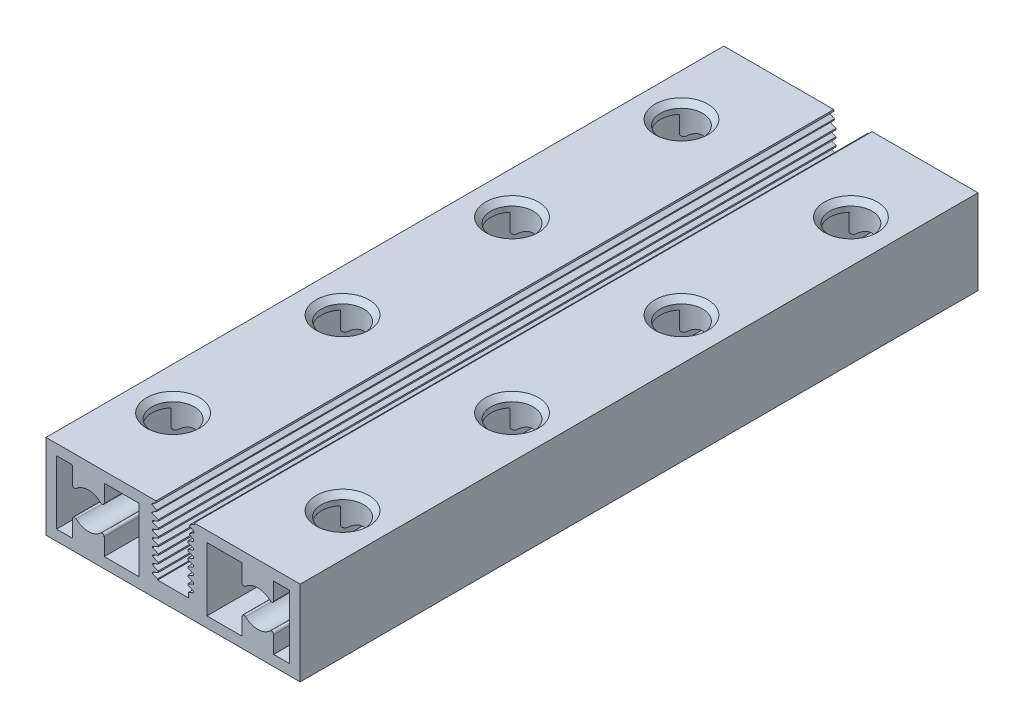
SolidWorks part; units mm, degrees
ref_plane "Front Plane" through (0, 0, 0) normal (0, 0, 1) x (1, 0, 0)
ref_plane "Top Plane" through (0, 0, 0) normal (0, 1, 0) x (1, 0, 0)
ref_plane "Right Plane" through (0, 0, 0) normal (1, 0, 0) x (0, 0, -1)
ref_plane "Plane1" through (0, 8, 0) normal (0, 1, 0) x (1, 0, 0)
sketch "Sketch1" plane through (0, 8, 0) normal (0, 1, 0) x (1, 0, 0)
  line L0 (12, -32) -> (-12, -32)
  line L1 (-12, -32) -> (-12, -96)
  line L2 (-12, -96) -> (12, -96)
  line L3 (12, -96) -> (12, -32)
extrude "Boss-Extrude1" add sketch "Sketch1" against normal blind 8
sketch "Sketch2" plane through (0, 0, 32) normal (0, 0, -1) x (-1, 0, 0)
  line L0 (1.62, 8) -> (-2, 8)
  line L1 (-2, 8) -> (-2, 7.88)
  line L2 (-2, 7.88) -> (-1.4684, 7.5731)
  line L3 (-1.4684, 7.5731) -> (-2.0747, 7.2231)
  line L4 (-2.0747, 7.2231) -> (-1.4684, 6.8731)
  line L5 (-1.4684, 6.8731) -> (-2.0878, 6.5155)
  line L6 (-2.0878, 6.5155) -> (-1.2404, 6.1731)
  line L7 (-1.2404, 6.1731) -> (-2.1067, 5.8231)
  line L8 (-2.1067, 5.8231) -> (-1.2404, 5.4731)
  line L9 (-1.2404, 5.4731) -> (-2.1067, 5.1231)
  line L10 (-2.1067, 5.1231) -> (-1.2404, 4.7731)
  line L11 (-1.2404, 4.7731) -> (-2.1067, 4.4231)
  line L12 (-2.1067, 4.4231) -> (-1.2404, 4.0731)
  line L13 (-1.2404, 4.0731) -> (-2.1067, 3.7231)
  line L14 (-2.1067, 3.7231) -> (-1.2404, 3.3731)
  line L15 (-1.2404, 3.3731) -> (-2.1067, 3.0231)
  line L16 (-2.1067, 3.0231) -> (-1.2404, 2.6731)
  line L17 (-1.2404, 2.6731) -> (-2.1067, 2.3231)
  line L18 (-2.1067, 2.3231) -> (-1.46, 2.0618)
  line L19 (-1.46, 2.0618) -> (-1.46, 1.6)
  line L20 (-1.46, 1.6) -> (1.46, 1.6)
  line L21 (1.46, 1.6) -> (1.46, 1.7012)
  line L22 (1.46, 1.7012) -> (2.1067, 1.9625)
  line L23 (2.1067, 1.9625) -> (1.2404, 2.3125)
  line L24 (1.2404, 2.3125) -> (2.1067, 2.6625)
  line L25 (2.1067, 2.6625) -> (1.2404, 3.0125)
  line L26 (1.2404, 3.0125) -> (2.1067, 3.3625)
  line L27 (2.1067, 3.3625) -> (1.2404, 3.7125)
  line L28 (1.2404, 3.7125) -> (2.1067, 4.0625)
  line L29 (2.1067, 4.0625) -> (1.2404, 4.4125)
  line L30 (1.2404, 4.4125) -> (2.1067, 4.7625)
  line L31 (2.1067, 4.7625) -> (1.2404, 5.1125)
  line L32 (1.2404, 5.1125) -> (2.1067, 5.4625)
  line L33 (2.1067, 5.4625) -> (1.2404, 5.8125)
  line L34 (1.2404, 5.8125) -> (2.1067, 6.1625)
  line L35 (2.1067, 6.1625) -> (1.2404, 6.5125)
  line L36 (1.2404, 6.5125) -> (2.0878, 6.8549)
  line L37 (2.0878, 6.8549) -> (1.4684, 7.2125)
  line L38 (1.4684, 7.2125) -> (2.0747, 7.5625)
  line L39 (2.0747, 7.5625) -> (1.62, 7.825)
  line L40 (1.62, 7.825) -> (1.62, 8)
extrude "Cut-Extrude1" cut sketch "Sketch2" against normal through all
sketch "Sketch3" plane through (0, 0, 96) normal (0, 0, 1) x (1, 0, 0)
  line L0 (9.5, 1) -> (11, 1)
  line L1 (11, 1) -> (11, 7)
  line L2 (11, 7) -> (9.5, 7)
  line L3 (9.5, 7) -> (9.5, 5.3856)
  line L4 (6.5, 5.3856) -> (6.5, 7)
  line L5 (6.5, 7) -> (3.2, 7)
  line L6 (3.2, 7) -> (3.2, 1)
  line L7 (3.2, 1) -> (6.5, 1)
  line L8 (6.5, 1) -> (6.5, 2.6144)
  line L9 (9.5, 2.6144) -> (9.5, 1)
  arc A0 (9.5, 5.3856) -> (9.1632, 5.2398) centre (9.3, 5.3856) cw
  arc A1 (9.1632, 5.2398) -> (6.8368, 5.2398) centre (8, 4) ccw
  arc A2 (6.8368, 5.2398) -> (6.5, 5.3856) centre (6.7, 5.3856) cw
  arc A3 (6.5, 2.6144) -> (6.8368, 2.7602) centre (6.7, 2.6144) cw
  arc A4 (6.8368, 2.7602) -> (9.1632, 2.7602) centre (8, 4) ccw
  arc A5 (9.1632, 2.7602) -> (9.5, 2.6144) centre (9.3, 2.6144) cw
extrude "Cut-Extrude2" cut sketch "Sketch3" against normal through all
sketch "Sketch4" plane through (0, 0, 32) normal (0, 0, -1) x (-1, 0, 0)
  line L0 (11, 7) -> (9.5, 7)
  line L1 (9.5, 7) -> (9.5, 5.3856)
  line L2 (6.5, 5.3856) -> (6.5, 7)
  line L3 (6.5, 7) -> (3.2, 7)
  line L4 (3.2, 7) -> (3.2, 1)
  line L5 (3.2, 1) -> (6.5, 1)
  line L6 (6.5, 1) -> (6.5, 2.6144)
  line L7 (9.5, 2.6144) -> (9.5, 1)
  line L8 (9.5, 1) -> (11, 1)
  line L9 (11, 1) -> (11, 7)
  arc A0 (9.5, 5.3856) -> (9.1632, 5.2398) centre (9.3, 5.3856) cw
  arc A1 (9.1632, 5.2398) -> (6.8368, 5.2398) centre (8, 4) ccw
  arc A2 (6.8368, 5.2398) -> (6.5, 5.3856) centre (6.7, 5.3856) cw
  arc A3 (6.5, 2.6144) -> (6.8368, 2.7602) centre (6.7, 2.6144) cw
  arc A4 (6.8368, 2.7602) -> (9.1632, 2.7602) centre (8, 4) ccw
  arc A5 (9.1632, 2.7602) -> (9.5, 2.6144) centre (9.3, 2.6144) cw
extrude "Cut-Extrude3" cut sketch "Sketch4" against normal through all
hole_wizard "Ø4.0 (4) Diameter Hole1" positions "Sketch6" profile "Sketch5" hole size "Ø4.0" standard "ANSI Metric"
sketch "Sketch6" plane through (0, 8, 0) normal (0, 1, 0) x (1, 0, 0)
  point P0 (-8, -88)
  point P1 (-8, -72)
  point P2 (-8, -56)
  point P3 (-8, -40)
  point P4 (8, -56)
  point P5 (8, -72)
  point P6 (8, -40)
  point P7 (8, -88)
sketch "Sketch5" plane through (-8, 8, 88) normal (1, 0, 0) x (0, 0, 1)
  line L0 (0, 0) -> (0, 10.8144)
  line L1 (0, 10.8144) -> (2, 10.8144)
  line L2 (2, 10.8144) -> (2, 0)
  line L5 (2, 0) -> (0, 0)
  line L10 (0, 10.8144) -> (-2, 10.8144) construction
  line L11 (0, -6.35) -> (0, 107.95) construction
  dimension "Hole Dia." = 4
  dimension "Hole Depth" = 10.8144
  dimension "Drill Angle" = 180
chamfer "Chamfer1" distance 0.1014 angle 60 6 edges at (2.0747, 7.2231, 64) (1.4684, 7.5731, 64) (-1.4684, 7.2125, 64) (-2.0747, 7.5625, 64) (1.4684, 6.8731, 64) (-2.0878, 6.8549, 64)
chamfer "Chamfer2" distance 0.169 angle 68 27 edges at (2.1067, 2.3231, 64) (2.1067, 5.1231, 64) (1.2404, 2.6731, 64) (-1.2404, 4.4125, 64) (1.2404, 4.7731, 64) (-1.2404, 5.1125, 64) (1.2404, 5.4731, 64) (-2.1067, 4.0625, 64) (2.1067, 4.4231, 64) (-2.1067, 5.4625, 64) (2.1067, 5.8231, 64) (-1.2404, 3.7125, 64) (-2.1067, 4.7625, 64) (1.2404, 4.0731, 64) (-1.2404, 2.3125, 64) (-1.2404, 5.8125, 64) (1.2404, 6.1731, 64) (-2.1067, 1.9625, 64) (-2.1067, 3.3625, 64) (2.1067, 3.7231, 64) (-2.1067, 6.1625, 64) (2.0878, 6.5155, 64) (-1.2404, 3.0125, 64) (1.2404, 3.3731, 64) (-1.2404, 6.5125, 64) (-2.1067, 2.6625, 64) (2.1067, 3.0231, 64)
chamfer "Chamfer3" distance 0.5 angle 45 16 edges at (-8, 0, 90) (-8, 8, 74) (8, 8, 74) (-8, 0, 58) (8, 8, 42) (-8, 8, 42) (-8, 0, 42) (-8, 0, 74) (8, 8, 58) (8, 8, 90) (-8, 8, 58) (-8, 8, 90) (8, 0, 42) (8, 0, 58) (8, 0, 74) (8, 0, 90)
